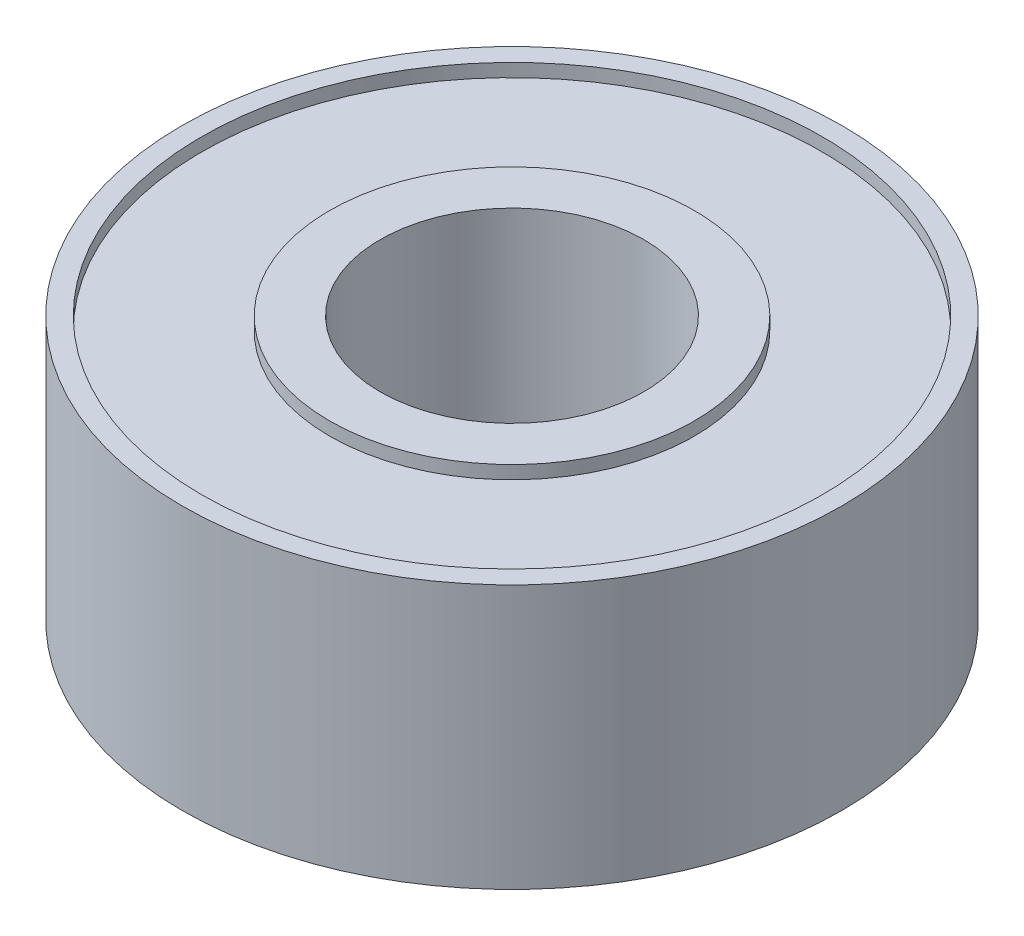
SolidWorks part; units mm, degrees
ref_plane "前视基准面" through (0, 0, 0) normal (0, 0, 1) x (1, 0, 0)
ref_plane "上视基准面" through (0, 0, 0) normal (0, 1, 0) x (1, 0, 0)
ref_plane "右视基准面" through (0, 0, 0) normal (1, 0, 0) x (0, 0, -1)
other "Configuration Table"
sketch "草图1" plane through (0, 0, 0) normal (0, 1, 0) x (1, 0, 0)
  circle A0 centre (0, 0) radius 1
  circle A1 centre (0, 0) radius 2.5
extrude "凸台-拉伸1" add sketch "草图1" along normal mid plane 2
sketch "草图2" plane through (0, 1, 0) normal (0, 1, 0) x (1, 0, 0)
  circle A0 centre (0, 0) radius 2.3524
  circle A1 centre (0, 0) radius 1.3825
extrude "切除-拉伸1" cut sketch "草图2" against normal blind 0.1
mirror "镜向1" about plane through (0, 0, 0) normal (0, 1, 0) of "切除-拉伸1"
